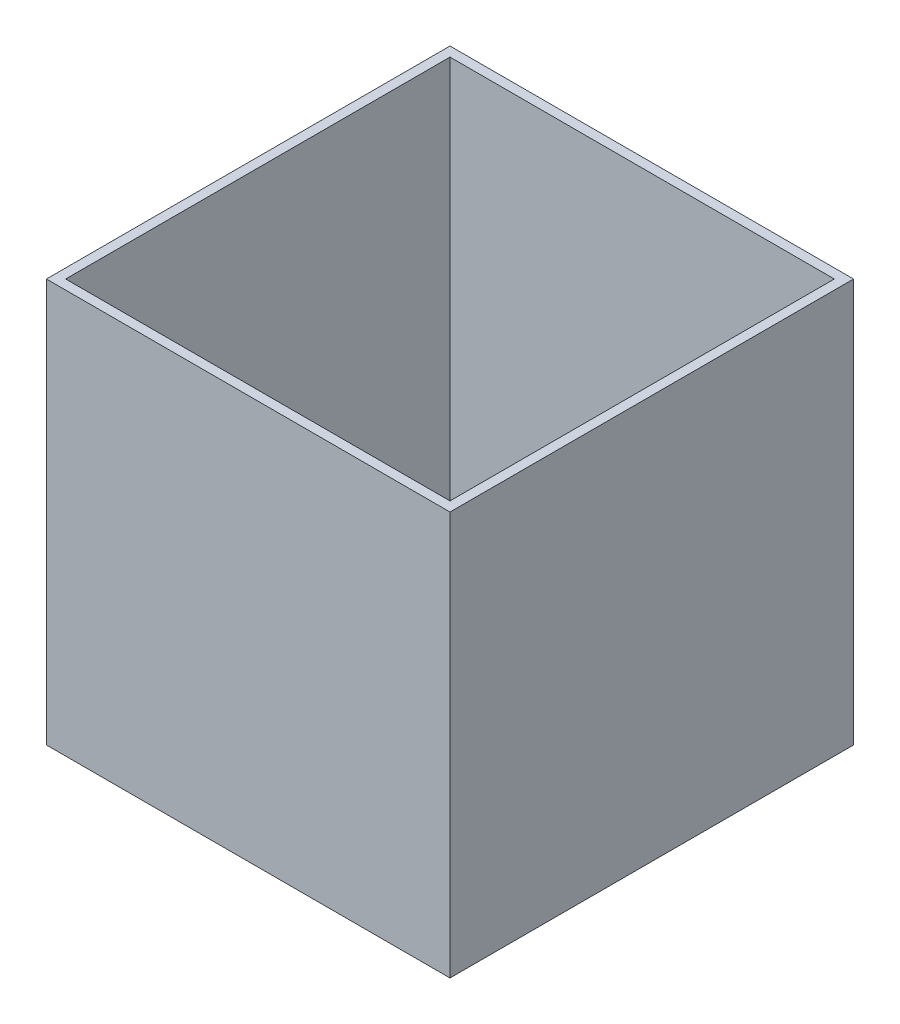
SolidWorks part; units mm, degrees
ref_plane "Front Plane" through (0, 0, 0) normal (0, 0, 1) x (1, 0, 0)
ref_plane "Top Plane" through (0, 0, 0) normal (0, 1, 0) x (1, 0, 0)
ref_plane "Right Plane" through (0, 0, 0) normal (1, 0, 0) x (0, 0, -1)
sketch "Sketch1" plane through (0, 0, 0) normal (0, 1, 0) x (1, 0, 0)
  line L1 (-21, 21) -> (21, 21)
  line L2 (-21, 21) -> (-21, -21)
  line L3 (-21, -21) -> (21, -21)
  line L4 (21, 21) -> (21, -21)
  line L5 (-21, 21) -> (21, -21) construction
  line L6 (-21, -21) -> (21, 21) construction
  point P0 (0, 0)
  dimension "D1" = 42
  dimension "4" = 42
extrude "Boss-Extrude2" add sketch "Sketch1" along normal blind 42
sketch "Sketch3" plane through (0, 42, 0) normal (0, 1, 0) x (1, 0, 0)
  line L1 (-20, 20) -> (20, 20)
  line L2 (-20, 20) -> (-20, -20)
  line L3 (-20, -20) -> (20, -20)
  line L4 (20, 20) -> (20, -20)
  line L5 (-20, 20) -> (20, -20) construction
  line L6 (-20, -20) -> (20, 20) construction
  point P0 (0, 0)
  dimension "D1" = 40
  dimension "D2" = 40
extrude "Cut-Extrude1" cut sketch "Sketch3" against normal blind 40
